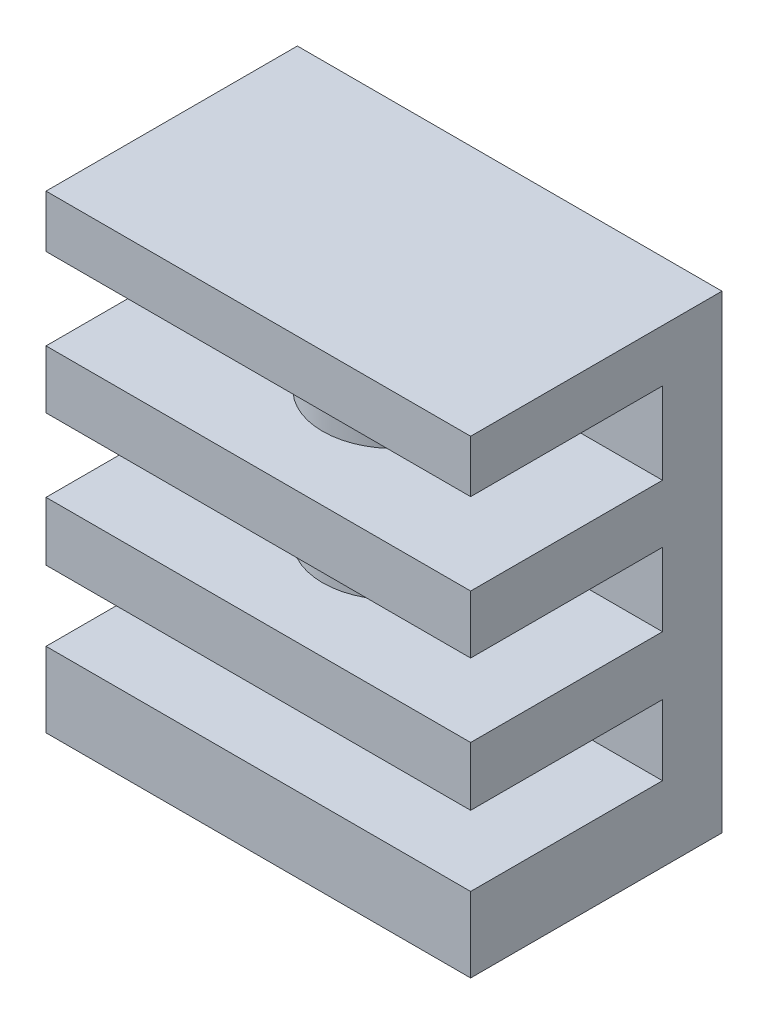
SolidWorks part; units mm, degrees
ref_plane "Front Plane" through (0, 0, 0) normal (0, 0, 1) x (1, 0, 0)
ref_plane "Top Plane" through (0, 0, 0) normal (0, 1, 0) x (1, 0, 0)
ref_plane "Right Plane" through (0, 0, 0) normal (1, 0, 0) x (0, 0, -1)
sketch "Sketch2" plane through (0, 0, 0) normal (1, 0, 0) x (0, 0, -1)
  line L0 (0, 0) -> (59.1881, 0)
  line L1 (59.1881, 0) -> (59.1881, 110.4958)
  line L2 (59.1881, 110.4958) -> (0, 110.4958)
  line L3 (0, 110.4958) -> (0, 98.173)
  line L4 (0, 98.173) -> (45.1772, 98.173)
  line L5 (45.1772, 98.173) -> (45.1772, 78.9291)
  line L6 (45.1772, 78.9291) -> (0, 78.9291)
  line L7 (0, 78.9291) -> (0, 65.2559)
  line L8 (0, 65.2559) -> (45.1772, 65.2559)
  line L9 (45.1772, 65.2559) -> (45.1772, 48.0377)
  line L10 (45.1772, 48.0377) -> (0, 48.0377)
  line L11 (0, 48.0377) -> (0, 34.1957)
  line L12 (0, 34.1957) -> (45.1772, 34.1957)
  line L13 (45.1772, 34.1957) -> (45.1772, 17.6527)
  line L14 (45.1772, 17.6527) -> (0, 17.6527)
  line L15 (0, 17.6527) -> (0, 0)
extrude "Boss-Extrude1" add sketch "Sketch2" along normal mid plane 100
sketch "Sketch4" plane through (0, 110.4958, 0) normal (0, 1, 0) x (1, 0, 0)
  circle A0 centre (0, 32.0218) radius 16.8908
extrude "Boss-Extrude2" add sketch "Sketch4" against normal up to vertex (62.458 mm away) up to point (-50, 48.0377, 0)
